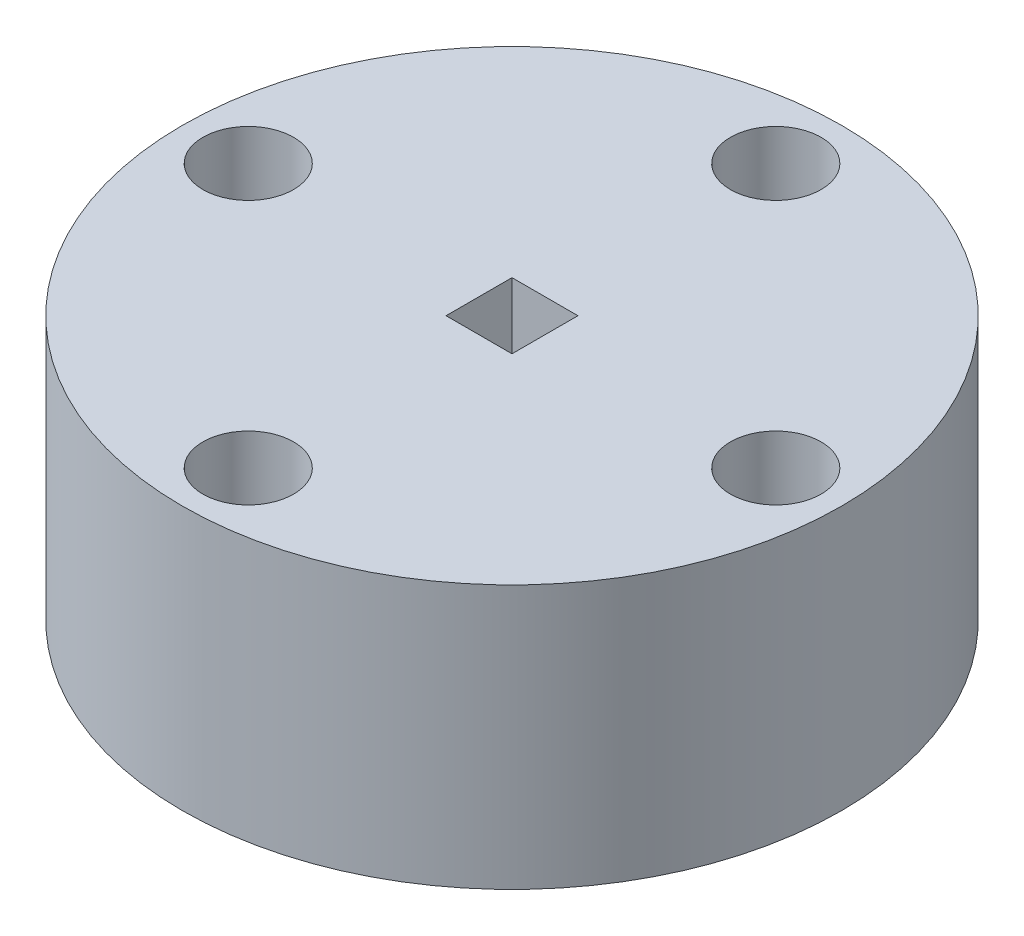
SolidWorks part; units mm, degrees
ref_plane "Front Plane" through (0, 0, 0) normal (0, 0, 1) x (1, 0, 0)
ref_plane "Top Plane" through (0, 0, 0) normal (0, 1, 0) x (1, 0, 0)
ref_plane "Right Plane" through (0, 0, 0) normal (1, 0, 0) x (0, 0, -1)
sketch "Sketch1" plane through (0, 0, 0) normal (0, 1, 0) x (1, 0, 0)
  line L1 (-1.5875, -1.5875) -> (1.5875, -1.5875)
  line L2 (-1.5875, -1.5875) -> (-1.5875, 1.5875)
  line L3 (-1.5875, 1.5875) -> (1.5875, 1.5875)
  line L4 (1.5875, -1.5875) -> (1.5875, 1.5875)
  line L5 (-1.5875, -1.5875) -> (1.5875, 1.5875) construction
  line L6 (-1.5875, 1.5875) -> (1.5875, -1.5875) construction
  circle A1 centre (12.7, 0) radius 2.1828
  circle A2 centre (-12.7, 0) radius 2.1828
  circle A3 centre (0, 0) radius 15.875
  circle A4 centre (0, 12.7) radius 2.1828
  circle A5 centre (0, -12.7) radius 2.1828
  dimension "D3" = 4.3656
  dimension "D4" = 3.175
  dimension "D5" = 4.3656
  dimension "D6" = 31.75
  dimension "D9" = 4.3656
  dimension "D10" = 4.3656
  dimension "D1" = 12.7
  dimension "D2" = 12.7
  dimension "D7" = 12.7
  dimension "D8" = 12.7
  dimension "D11" = 3.175
extrude "Boss-Extrude1" add sketch "Sketch1" along normal blind 12.7
